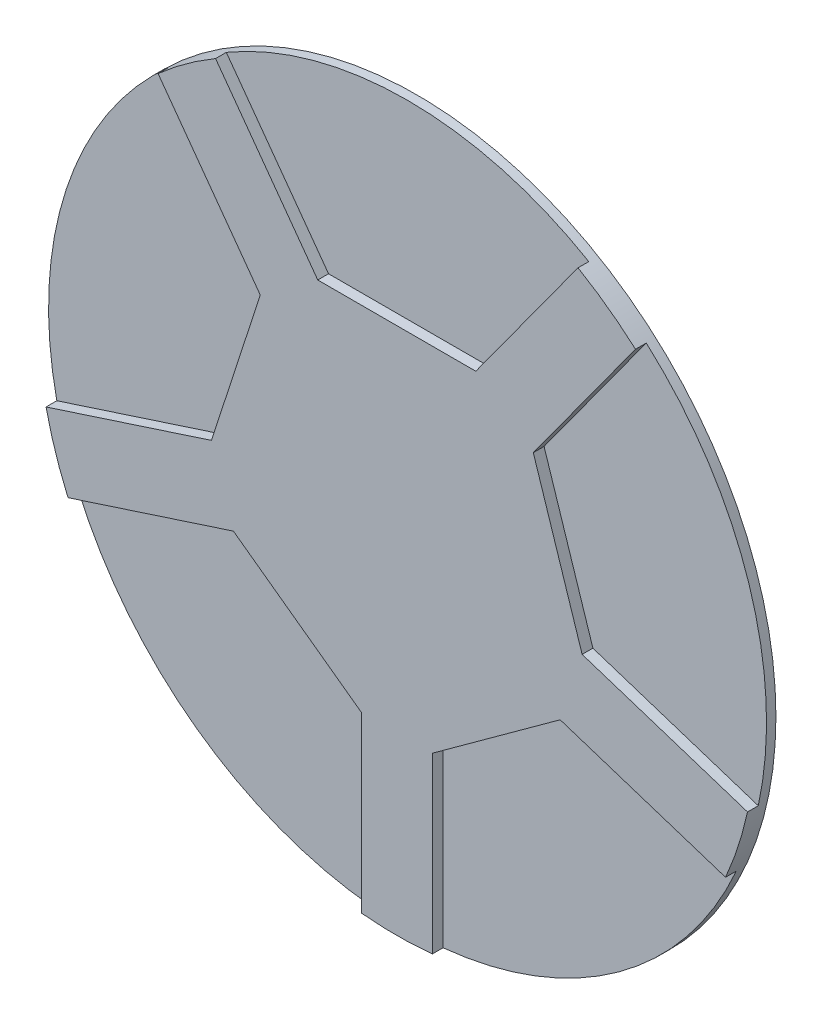
SolidWorks part; units mm, degrees
ref_plane "Front Plane" through (0, 0, 0) normal (0, 0, 1) x (1, 0, 0)
ref_plane "Top Plane" through (0, 0, 0) normal (0, 1, 0) x (1, 0, 0)
ref_plane "Right Plane" through (0, 0, 0) normal (1, 0, 0) x (0, 0, -1)
sketch "Sketch1" plane through (0, 0, 0) normal (0, 0, 1) x (1, 0, 0)
  circle A0 centre (0, 0) radius 213.711
extrude "Boss-Extrude1" add sketch "Sketch1" along normal blind 12
sketch "Sketch2" plane through (0, 0, 12) normal (0, 0, 1) x (1, 0, 0)
  line L5 (0, 63.711) -> (0, -0.9357) construction
  line L7 (-47.0405, 100.7363) -> (47.0405, 100.7363)
  line L8 (-107.8847, 184.4811) -> (-47.0405, 100.7363)
  line L9 (107.8847, 184.4811) -> (47.0405, 100.7363)
  circle A0 centre (0, 0) radius 213.711 construction
  arc A5 (-107.8847, 184.4811) -> (107.8847, 184.4811) centre (0, 0) cw
  dimension "D2" = 54
extrude "Cut-Extrude1" cut sketch "Sketch2" against normal blind 6.405
sketch "Sketch4" plane through (0, 0, 0) normal (0, 1, 0) x (1, 0, 0)
  line L0 (0, -12.3908) -> (0, 0) construction
pattern_circular "CirPattern1" count 5 every 72 about axis through (0, 0, 0) along (0, 0, 1) of "Cut-Extrude1"
sketch "Sketch5" plane through (0, 0, 12) normal (0, 0, 1) x (1, 0, 0)
  circle A0 centre (0, 0) radius 31.75
